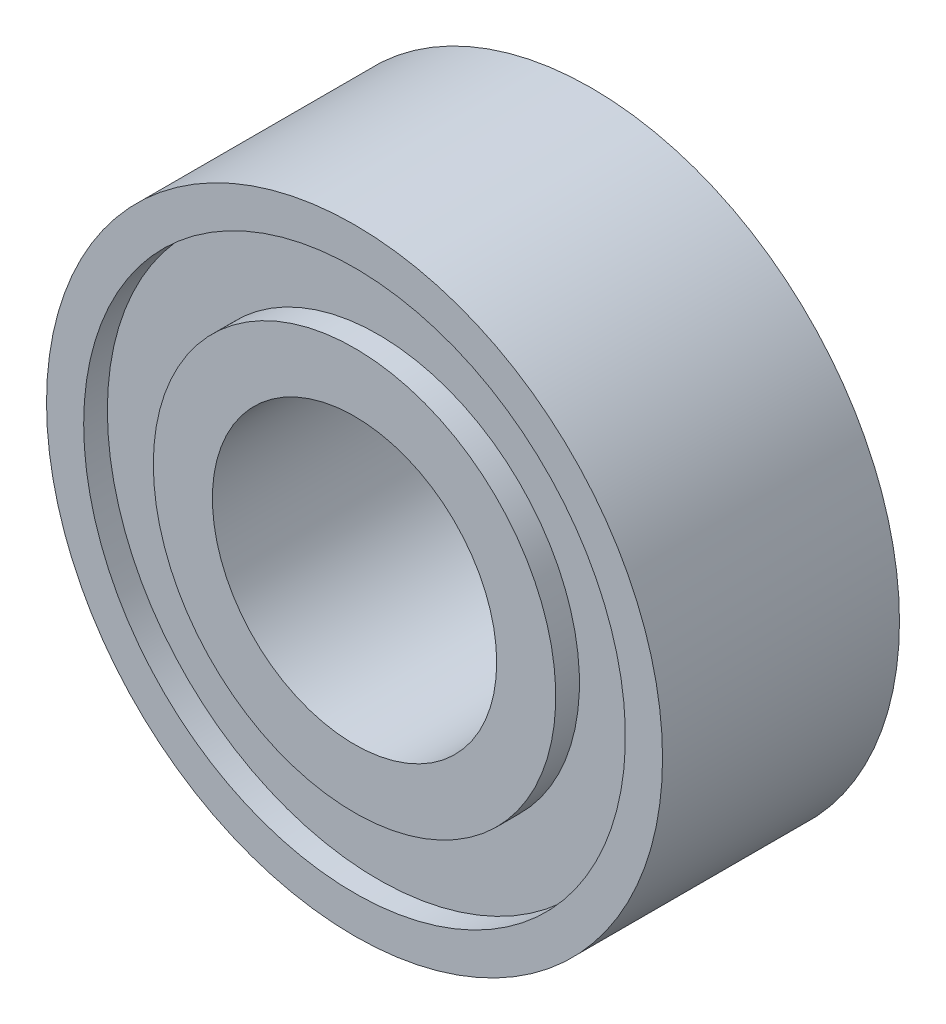
SolidWorks part; units mm, degrees
ref_plane "前视基准面" through (0, 0, 0) normal (0, 0, 1) x (1, 0, 0)
ref_plane "上视基准面" through (0, 0, 0) normal (0, 1, 0) x (1, 0, 0)
ref_plane "右视基准面" through (0, 0, 0) normal (1, 0, 0) x (0, 0, -1)
sketch "草图1" plane through (0, 0, 0) normal (0, 0, 1) x (1, 0, 0)
  circle A0 centre (0, 0) radius 6.5
  circle A1 centre (0, 0) radius 3
  dimension "D1" = 13
  dimension "D2" = 6
extrude "凸台-拉伸1" add sketch "草图1" along normal mid plane 5
sketch "草图2" plane through (0, 0, -2.5) normal (0, 0, -1) x (-1, 0, 0)
  circle A0 centre (0, 0) radius 4.2462
  circle A1 centre (0, 0) radius 5.7161
extrude "切除-拉伸1" cut sketch "草图2" against normal blind 0.5
mirror "镜向1" about plane through (0, 0, 0) normal (0, 0, 1) of "切除-拉伸1"
